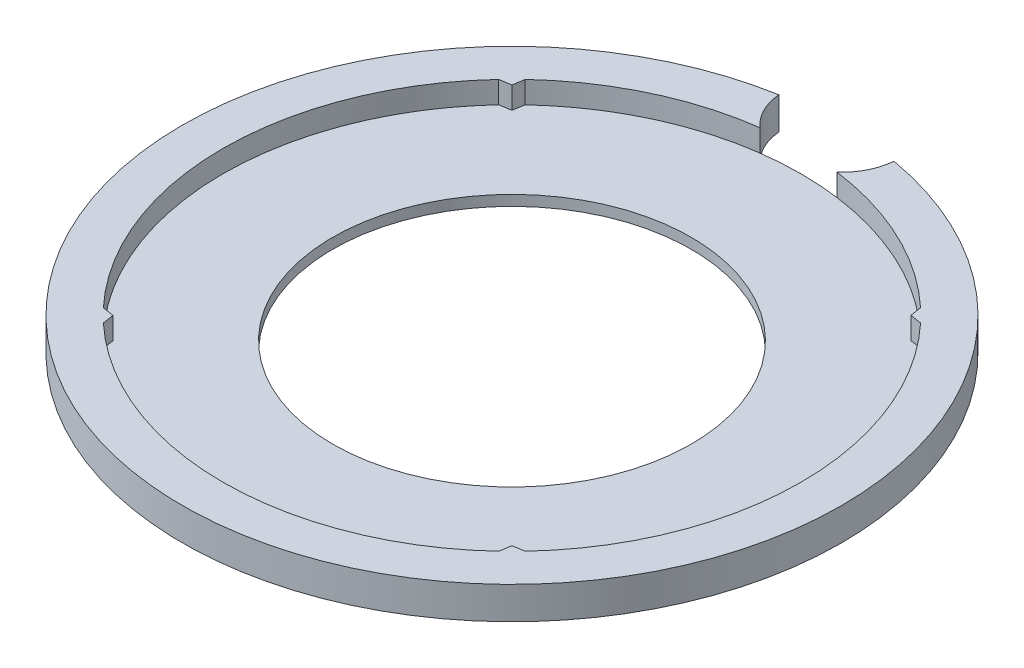
SolidWorks part; units mm, degrees
ref_plane "Front Plane" through (0, 0, 0) normal (0, 0, 1) x (1, 0, 0)
ref_plane "Top Plane" through (0, 0, 0) normal (0, 1, 0) x (1, 0, 0)
ref_plane "Right Plane" through (0, 0, 0) normal (1, 0, 0) x (0, 0, -1)
sketch "Sketch1" plane through (0, 0, 0) normal (0, 1, 0) x (1, 0, 0)
  circle A0 centre (0, 0) radius 25
  circle A1 centre (0, 0) radius 15.5
  dimension "D1" = 50
  dimension "D2" = 31
extrude "Boss-Extrude1" add sketch "Sketch1" along normal blind 0.9
sketch "Sketch2" plane through (0, 0, 0) normal (0, -1, 0) x (1, 0, 0)
  circle A0 centre (0, 0) radius 28.5
  circle A1 centre (0, 0) radius 25
  circle A2 centre (0, 0) radius 25
  dimension "D2" = 3.5
  dimension "D1" = 0
extrude "Boss-Extrude2" add sketch "Sketch2" against normal blind 2.8 separate body
sketch "Sketch3" plane through (0, 2.8, 0) normal (0, 1, 0) x (1, 0, 0)
  line L5 (0, 0) -> (0, 25) construction
  circle A2 centre (0, 0) radius 25 construction
  circle A3 centre (0, 28.5) radius 5
  circle A4 centre (0, 0) radius 28.5 construction
  dimension "D1" = 10
extrude "Cut-Extrude1" cut sketch "Sketch3" against normal through all both and the other way through all
sketch "Sketch4" plane through (0, 2.8, 0) normal (0, 1, 0) x (1, 0, 0)
  line L0 (25, 0) -> (24.4, 0) construction
  line L1 (24.4, 0) -> (24.9869, -0.8097)
  line L2 (24.4, 0) -> (24.9869, 0.8097)
  line L3 (17.2534, -17.2534) -> (17.0959, -18.2409)
  line L4 (17.2534, -17.2534) -> (18.2409, -17.0959)
  line L5 (17.6777, -17.6777) -> (17.2534, -17.2534) construction
  line L6 (0, -24.4) -> (-0.8097, -24.9869)
  line L7 (0, -24.4) -> (0.8097, -24.9869)
  line L8 (0, -25) -> (0, -24.4) construction
  line L9 (-17.2534, -17.2534) -> (-18.2409, -17.0959)
  line L10 (-17.2534, -17.2534) -> (-17.0959, -18.2409)
  line L11 (-17.6777, -17.6777) -> (-17.2534, -17.2534) construction
  line L12 (-24.4, 0) -> (-24.9869, 0.8097)
  line L13 (-24.4, 0) -> (-24.9869, -0.8097)
  line L14 (-25, 0) -> (-24.4, 0) construction
  line L15 (-17.2534, 17.2534) -> (-17.0959, 18.2409)
  line L16 (-17.2534, 17.2534) -> (-18.2409, 17.0959)
  line L17 (-17.6777, 17.6777) -> (-17.2534, 17.2534) construction
  line L18 (0, 24.4) -> (0.8097, 24.9869)
  line L19 (0, 24.4) -> (-0.8097, 24.9869)
  line L20 (0, 25) -> (0, 24.4) construction
  line L21 (17.2534, 17.2534) -> (18.2409, 17.0959)
  line L22 (17.2534, 17.2534) -> (17.0959, 18.2409)
  line L23 (17.6777, 17.6777) -> (17.2534, 17.2534) construction
  arc A0 (-3.3368, 24.7763) -> (3.3368, 24.7763) centre (0, 0) ccw construction
  circle A1 centre (0, 0) radius 25 construction
  arc A2 (24.9869, -0.8097) -> (24.9869, 0.8097) centre (0, 0) ccw
  arc A3 (17.0959, -18.2409) -> (18.2409, -17.0959) centre (0, 0) ccw
  arc A4 (-0.8097, -24.9869) -> (0.8097, -24.9869) centre (0, 0) ccw
  arc A5 (-18.2409, -17.0959) -> (-17.0959, -18.2409) centre (0, 0) ccw
  arc A6 (-24.9869, 0.8097) -> (-24.9869, -0.8097) centre (0, 0) ccw
  arc A7 (-17.0959, 18.2409) -> (-18.2409, 17.0959) centre (0, 0) ccw
  arc A8 (0.8097, 24.9869) -> (-0.8097, 24.9869) centre (0, 0) ccw
  arc A9 (18.2409, 17.0959) -> (17.0959, 18.2409) centre (0, 0) ccw
  point P43 (0, 0)
  arc M35 (3.3368, 24.7763) -> (-3.3368, 24.7763) centre (0, 0) cw
  dimension "D1" = 0.6
  dimension "D2" = 1
  dimension "D3" = 1
  dimension "D4" = 8
extrude "Boss-Extrude3" add sketch "Sketch4" against normal up to surface (2.8 mm away) contours L22 L21 M35 | L4 L3 M35 | L10 L9 M35 | L16 A7 L15 up to face at (0, 0, 0.2438)
